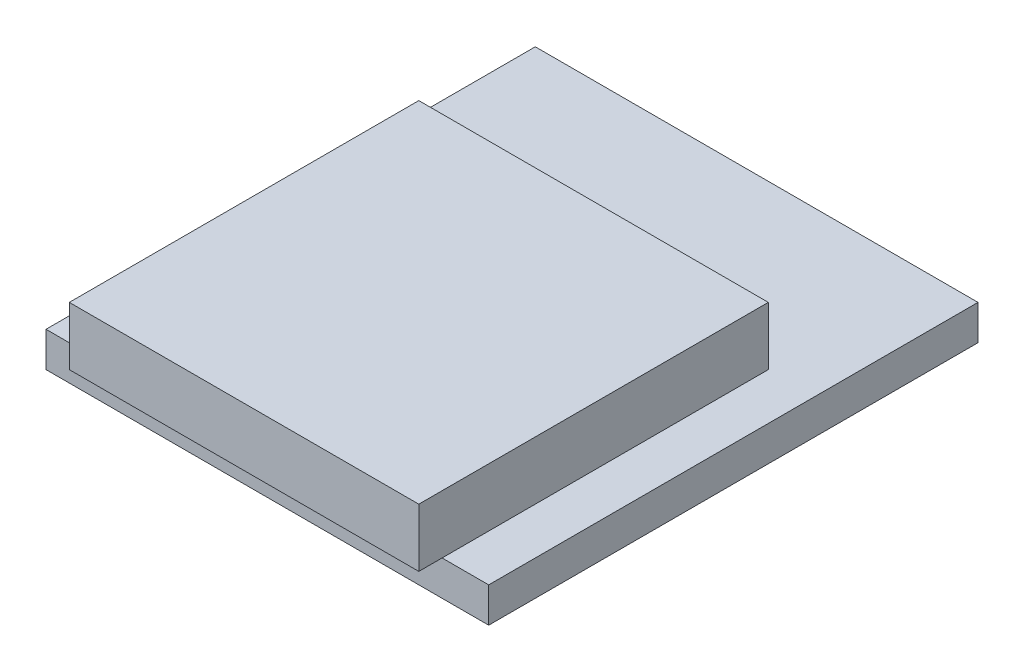
SolidWorks part; units mm, degrees
ref_plane "Front Plane" through (0, 0, 0) normal (0, 0, 1) x (1, 0, 0)
ref_plane "Top Plane" through (0, 0, 0) normal (0, 1, 0) x (1, 0, 0)
ref_plane "Right Plane" through (0, 0, 0) normal (1, 0, 0) x (0, 0, -1)
sketch "Sketch1" plane through (0, 0, 0) normal (0, 1, 0) x (1, 0, 0)
  line L1 (-7.5, 7.5) -> (7.5, 7.5)
  line L2 (-7.5, 7.5) -> (-7.5, -7.5)
  line L3 (-7.5, -7.5) -> (7.5, -7.5)
  line L4 (7.5, 7.5) -> (7.5, -7.5)
  line L5 (-7.5, 7.5) -> (7.5, -7.5) construction
  line L6 (-7.5, -7.5) -> (7.5, 7.5) construction
  point P0 (0, 0)
  dimension "D1" = 15
  dimension "D2" = 15
extrude "Boss-Extrude1" add sketch "Sketch1" along normal blind 2.5
sketch "Sketch2" plane through (0, 0, 0) normal (0, -1, 0) x (1, 0, 0)
  line L0 (7.5, 7.5) -> (7.5, -7.5) construction
  line L1 (9.5, 6.5) -> (-9.5, 6.5)
  line L2 (9.5, 6.5) -> (9.5, -14.5)
  line L3 (9.5, -14.5) -> (-9.5, -14.5)
  line L4 (-9.5, 6.5) -> (-9.5, -14.5)
  line L5 (-7.5, -7.5) -> (-7.5, 7.5) construction
  line L6 (7.5, -7.5) -> (-7.5, -7.5) construction
  line L7 (-7.5, 7.5) -> (7.5, 7.5) construction
  point P10 (0, -7.5)
  dimension "D1" = 2
  dimension "D2" = 2
  dimension "D3" = 7
  dimension "D4" = 1
extrude "Boss-Extrude2" add sketch "Sketch2" along normal blind 1.5
